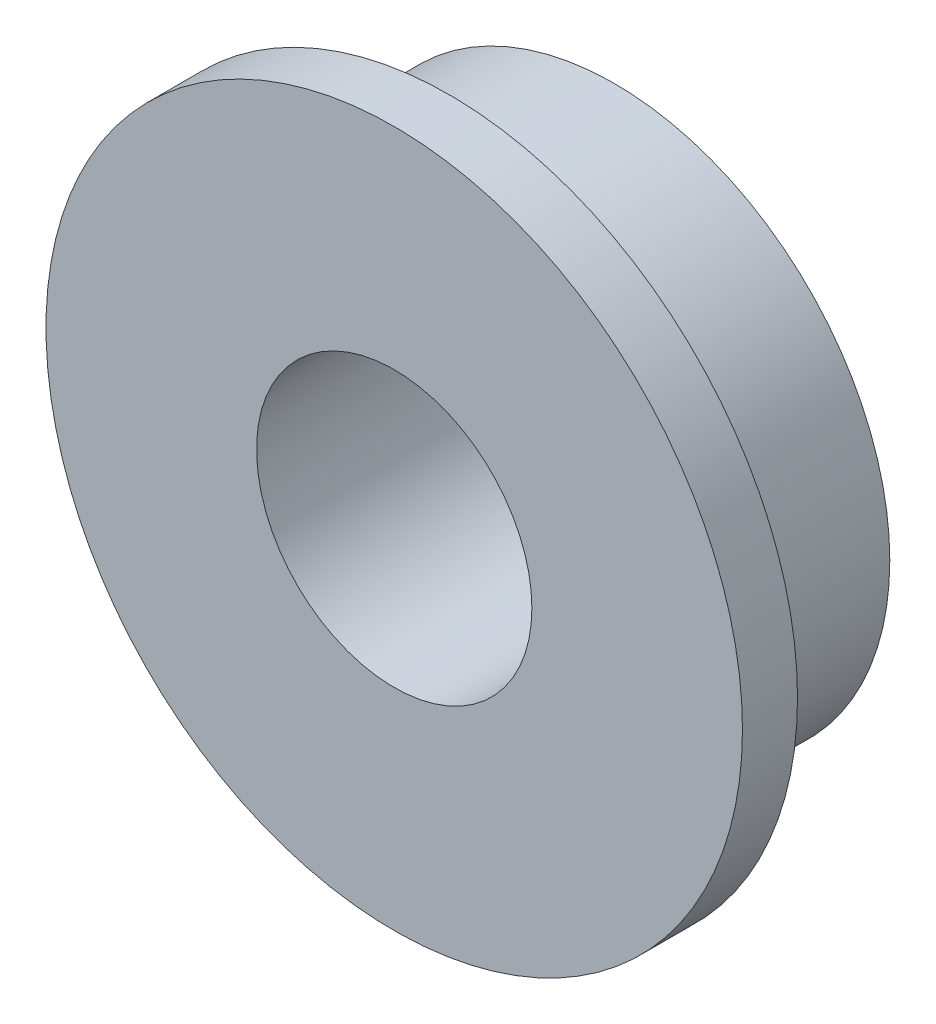
SolidWorks part; units mm, degrees
ref_plane "前视基准面" through (0, 0, 0) normal (0, 0, 1) x (1, 0, 0)
ref_plane "上视基准面" through (0, 0, 0) normal (0, 1, 0) x (1, 0, 0)
ref_plane "右视基准面" through (0, 0, 0) normal (1, 0, 0) x (0, 0, -1)
sketch "草图1" plane through (0, 0, 0) normal (0, 0, 1) x (1, 0, 0)
  circle A0 centre (0.6905, 1.4689) radius 2.5
  circle A1 centre (0.6905, 1.4689) radius 5
  dimension "D1" = 5
  dimension "D2" = 10
extrude "凸台-拉伸1" add sketch "草图1" along normal blind 4
sketch "草图2" plane through (0, 0, 4) normal (0, 0, 1) x (1, 0, 0)
  circle A0 centre (0.6905, 1.4689) radius 6.3242
  circle A1 centre (0.6905, 1.4689) radius 2.5
extrude "凸台-拉伸2" add sketch "草图2" against normal blind 1
